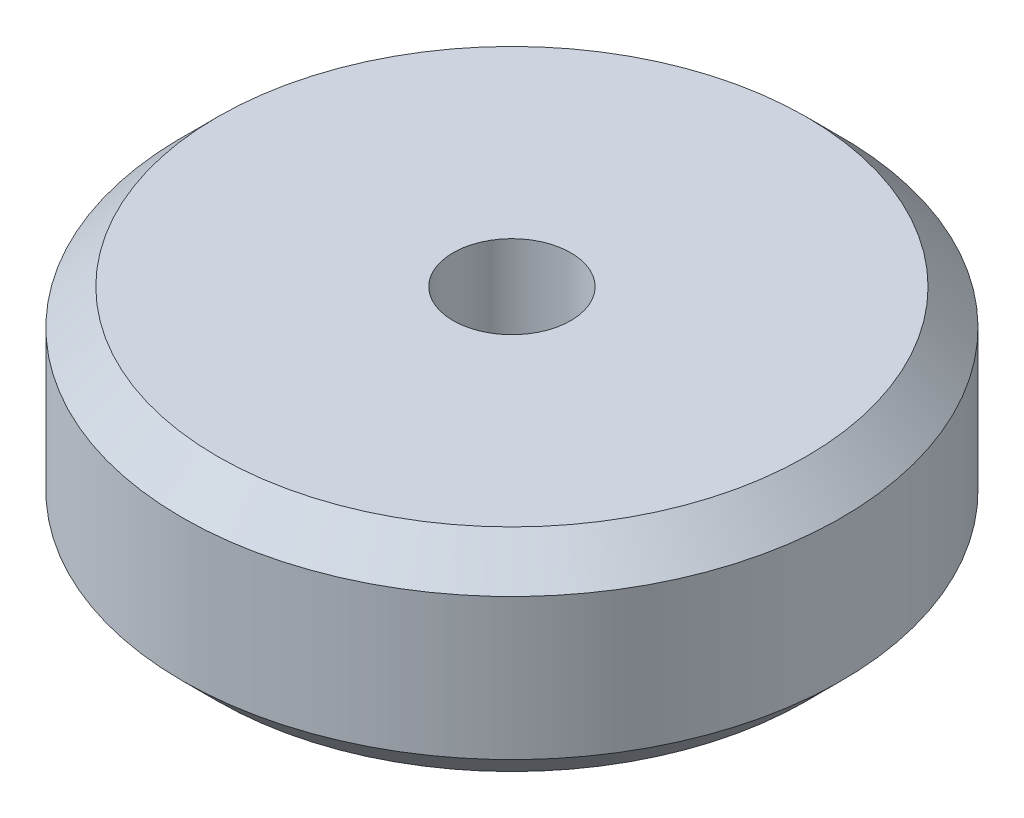
SolidWorks part; units mm, degrees
material "Rubber"
ref_plane "Front Plane" through (0, 0, 0) normal (0, 0, 1) x (1, 0, 0)
ref_plane "Top Plane" through (0, 0, 0) normal (0, 1, 0) x (1, 0, 0)
ref_plane "Right Plane" through (0, 0, 0) normal (1, 0, 0) x (0, 0, -1)
sketch "Sketch1" plane through (0, 0, 0) normal (0, 1, 0) x (1, 0, 0)
  circle A0 centre (0, 0) radius 2.5
  circle A1 centre (0, 0) radius 14
  dimension "D1" = 5
  dimension "D2" = 28
extrude "Boss-Extrude1" add sketch "Sketch1" along normal blind 9
chamfer "Chamfer1" distance 1.5 angle 45 2 edges at (0, 0, 14) (0, 9, 14)
